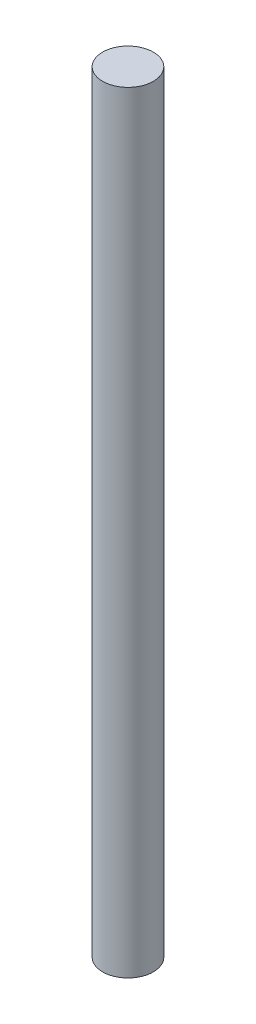
SolidWorks part; units mm, degrees
ref_plane "前基準面" through (0, 0, 0) normal (0, 0, 1) x (1, 0, 0)
ref_plane "上基準面" through (0, 0, 0) normal (0, 1, 0) x (1, 0, 0)
ref_plane "右基準面" through (0, 0, 0) normal (1, 0, 0) x (0, 0, -1)
sketch "草圖1" plane through (0, 0, 0) normal (0, 1, 0) x (1, 0, 0)
  circle A0 centre (0, 0) radius 11.5
  dimension "D1" = 23
extrude "填料-伸長1" add sketch "草圖1" along normal blind 350
